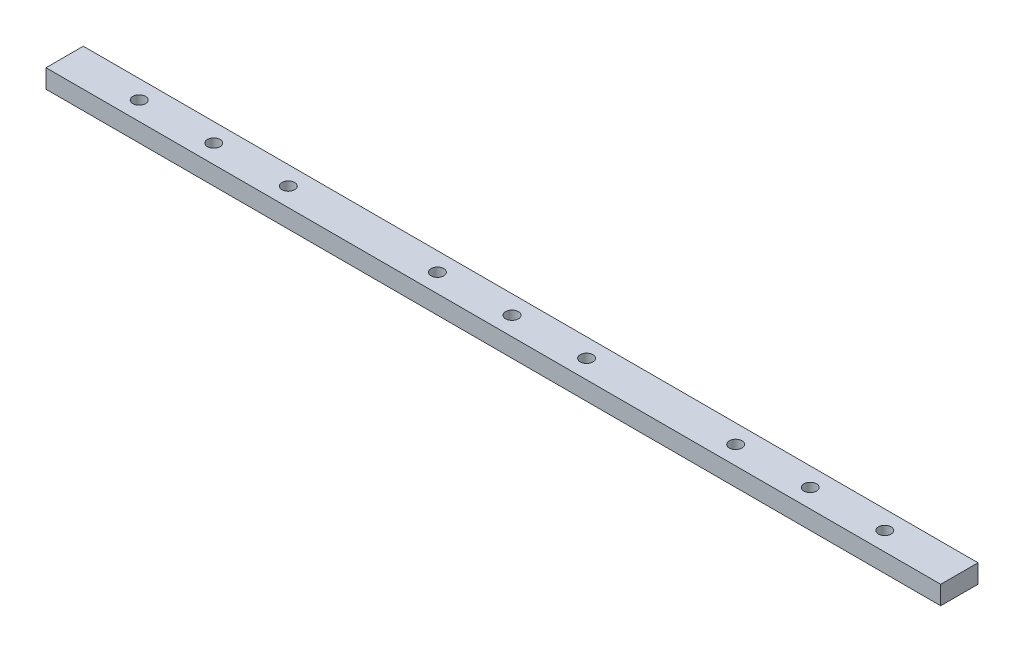
SolidWorks part; units mm, degrees
ref_plane "前视基准面" through (0, 0, 0) normal (0, 0, 1) x (1, 0, 0)
ref_plane "上视基准面" through (0, 0, 0) normal (0, 1, 0) x (1, 0, 0)
ref_plane "右视基准面" through (0, 0, 0) normal (1, 0, 0) x (0, 0, -1)
other "Configuration Table"
sketch "草图1" plane through (0, 0, 0) normal (0, 1, 0) x (1, 0, 0)
  line L0 (0, 5) -> (240, 5) construction
  line L1 (0, 0) -> (240, 0)
  line L2 (0, 0) -> (0, 10)
  line L3 (0, 10) -> (240, 10)
  line L4 (240, 0) -> (240, 10)
  line L5 (120, 0) -> (120, 10) construction
  circle A1 centre (20, 5) radius 1.7
  circle A2 centre (40, 5) radius 1.7
  circle A3 centre (120, 5) radius 1.7
  circle A6 centre (60, 5) radius 1.7
  circle A8 centre (100, 5) radius 1.7
  circle A9 centre (140, 5) radius 1.7
  circle A10 centre (180, 5) radius 1.7
  circle A11 centre (200, 5) radius 1.7
  circle A12 centre (220, 5) radius 1.7
  point P16 (120, 5)
  point P20 (150, 5)
  dimension "D6" = 20
  dimension "D7" = 3.4
  dimension "D1" = 240
  dimension "D2" = 10
  dimension "D3" = 40
  dimension "D4" = 40
  dimension "D5" = 20
extrude "凸台-拉伸1" add sketch "草图1" along normal blind 5
